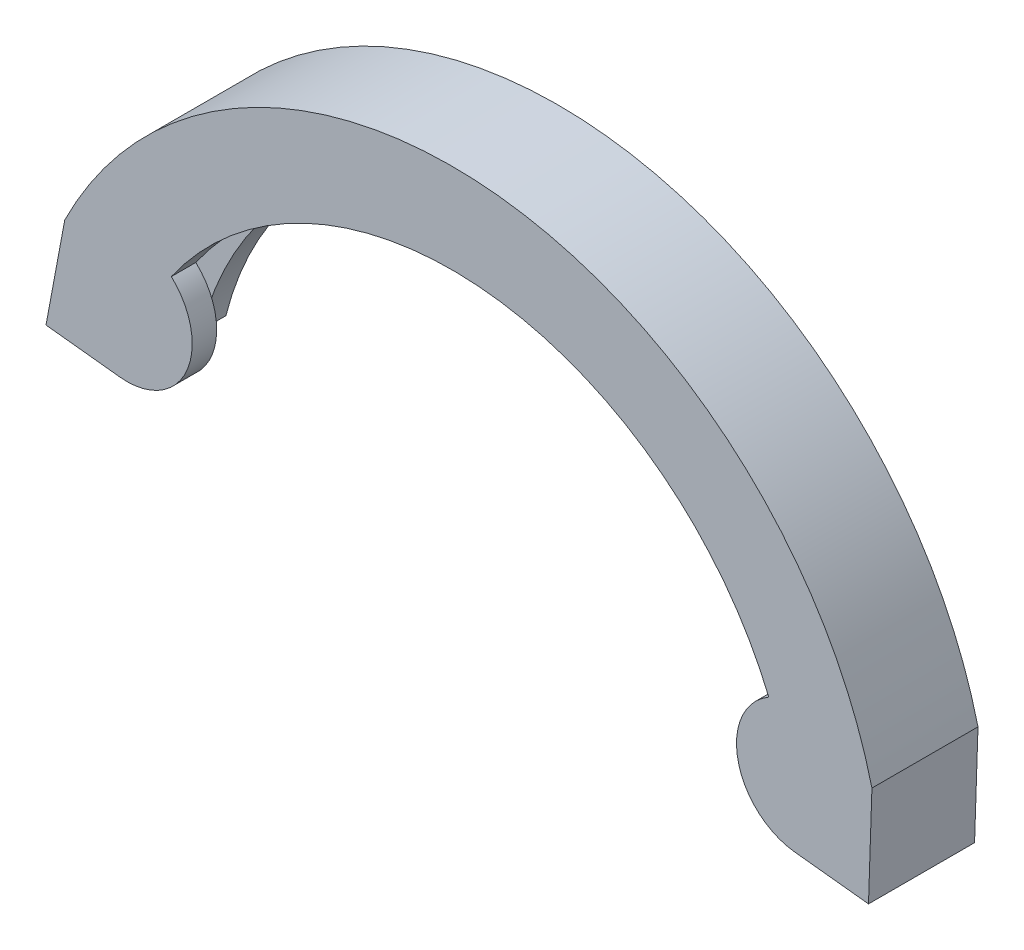
SolidWorks part; units mm, degrees
ref_plane "Front Plane" through (0, 0, 0) normal (0, 0, 1) x (1, 0, 0)
ref_plane "Top Plane" through (0, 0, 0) normal (0, 1, 0) x (1, 0, 0)
ref_plane "Right Plane" through (0, 0, 0) normal (1, 0, 0) x (0, 0, -1)
sketch "Sketch1" plane through (0, 0, 0) normal (0, 1, 0) x (1, 0, 0)
  line L1 (0, 0) -> (50, 0)
  line L2 (0, 0) -> (0, 7)
  line L3 (0, 7) -> (50, 7)
  line L4 (50, 0) -> (50, 7)
revolve "Revolve5" add sketch "Sketch1" angle 167.5 about L2
sketch "Sketch8" plane through (0, 0, 0) normal (0, 0, 1) x (1, 0, 0)
  line L0 (-48.8148, 10.822) -> (50, 0) construction
sketch "Sketch9" plane through (0, 0, -7) normal (0, 0, -1) x (-1, 0, 0)
  line L0 (-50, 0) -> (48.8148, 10.822) construction
shell "Shell2" thickness 3
sketch "Sketch11" plane through (0, 0, 3) normal (0, 0, 1) x (1, 0, 0)
  line L0 (-51.7437, 11.4713) -> (53, 0)
extrude "Cut-Extrude3" cut sketch "Sketch11" against normal blind 10 and the other way through all flip side to cut contours L0
sketch "Sketch12" plane through (0, 0, -10) normal (0, 0, -1) x (-1, 0, 0)
  line L0 (-53, 0) -> (51.7437, 11.4713)
extrude "Cut-Extrude4" cut sketch "Sketch12" against normal blind 10 and the other way through all flip side to cut contours L0
sketch "Sketch13" plane through (0, 0, -10) normal (0, 0, -1) x (-1, 0, 0)
  line L0 (-50, 0) -> (48.8148, 10.822) construction
  line L1 (-50, 0) -> (-55.7837, 52.8108) construction
  line L2 (48.8148, 10.822) -> (43.0311, 63.6327) construction
  line L3 (-55.7837, 52.8108) -> (43.0311, 63.6327) construction
  line L4 (48.7792, 11.1466) -> (47.4197, 23.5606)
  line L6 (-50.0356, 0.3247) -> (-51.3951, 12.7389)
extrude "Cut-Extrude-Thin1" cut sketch "Sketch13" against normal blind 20 and the other way through all flip side to cut thin contours L4
sketch "Sketch14" plane through (0, 0, -10) normal (0, 0, -1) x (-1, 0, 0)
  line L4 (-50.0356, 0.3247) -> (-51.3941, 12.7294)
  line L5 (48.7792, 11.1466) -> (-53, 0) construction
extrude "Cut-Extrude-Thin2" cut sketch "Sketch14" against normal blind 20 and the other way through all thin contours L4 thin type one direction reverse wall 30
sketch "Sketch15" plane through (0, 0, -10) normal (0, 0, -1) x (-1, 0, 0)
  line L0 (48.7792, 11.1466) -> (47.4197, 23.5606) construction
  line L1 (48.7792, 11.1466) -> (-50.0356, 0.3247) construction
  arc A0 (-50.0356, 0.3247) -> (48.7792, 11.1466) centre (0, 0) cw construction
  arc A1 (-41.9827, 1.2066) -> (40.7264, 10.2647) centre (0, 0) cw
extrude "Cut-Extrude-Thin3" cut sketch "Sketch15" against normal blind 20 and the other way through all thin contours A1
sketch "Sketch18" plane through (0, 0, 3) normal (0, 0, 1) x (1, 0, 0)
  line L0 (-40.7264, 10.2647) -> (41.9827, 1.2066) construction
  line L1 (-40.7264, 10.2647) -> (-39.8554, 18.2172) construction
  line L2 (41.9827, 1.2066) -> (42.8536, 9.159) construction
  line L3 (-39.8554, 18.2172) -> (42.8536, 9.159) construction
  circle A4 centre (-39.8554, 18.2172) radius 8
  circle A6 centre (42.8536, 9.159) radius 8
extrude "Boss-Extrude3" add sketch "Sketch18" against normal blind 3 contours A6 | A4
sketch "Sketch21" plane through (0, 0, 3) normal (0, 0, 1) x (1, 0, 0)
  line L0 (-40.7264, 10.2647) -> (41.9827, 1.2066) construction
  line L1 (-40.7264, 10.2647) -> (-39.8641, 18.1381) construction
  line L2 (41.9827, 1.2066) -> (42.8449, 9.08) construction
  line L3 (-39.8641, 18.1381) -> (42.8449, 9.08) construction
  circle A0 centre (-40, 18.2) radius 8 construction
  circle A1 centre (42.8449, 9.08) radius 8.0795 construction
sketch "Sketch22" plane through (-49.4074, 5.411, 0) normal (-0.9941, 0.1089, 0) x (0, 0, 1)
  line L1 (-10, 5.7699) -> (3, 5.7699)
  line L2 (-10, 5.7699) -> (-10, 18.2581)
  line L3 (-10, 18.2581) -> (3, 18.2581)
  line L4 (3, 5.7699) -> (3, 18.2581)
extrude "Boss-Extrude4" add sketch "Sketch22" along normal blind 1
sketch "Sketch23" plane through (49.4074, -5.411, 0) normal (0.9941, -0.1089, 0) x (0, 0, -1)
  line L1 (-3, 5.7699) -> (10, 5.7699)
  line L2 (-3, 5.7699) -> (-3, 18.2489)
  line L3 (-3, 18.2489) -> (10, 18.2489)
  line L4 (10, 5.7699) -> (10, 18.2489)
extrude "Boss-Extrude5" add sketch "Sketch23" along normal blind 1
sketch "Sketch25" plane through (0, 0, -10) normal (0, 0, -1) x (-1, 0, 0)
  line L0 (-51.4502, 12.7233) -> (-51.0296, 0.2158)
extrude "Cut-Extrude-Thin4" cut sketch "Sketch25" against normal blind 20 and the other way through all flip side to cut thin contours L0
sketch "Sketch26" plane through (0, 0, 3) normal (0, 0, 1) x (1, 0, 0)
  line L0 (-47.4724, 23.5663) -> (-49.7733, 11.2555)
extrude "Cut-Extrude-Thin5" cut sketch "Sketch26" against normal blind 20 and the other way through all flip side to cut thin contours L0
